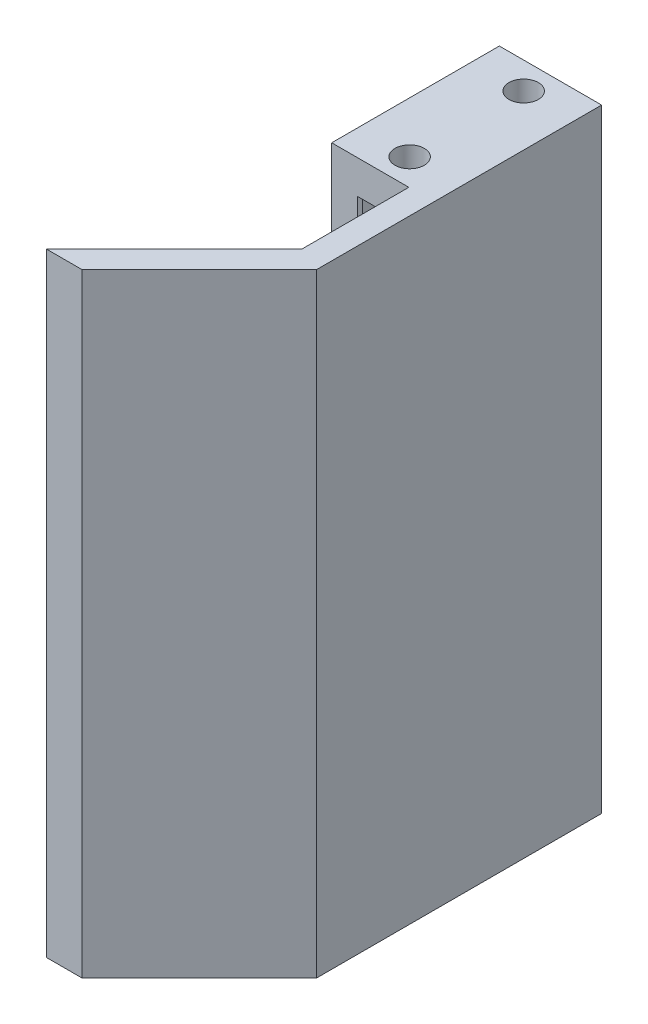
SolidWorks part; units mm, degrees
material "ABS"
ref_plane "前视基准面" through (0, 0, 0) normal (0, 0, 1) x (1, 0, 0)
ref_plane "上视基准面" through (0, 0, 0) normal (0, 1, 0) x (1, 0, 0)
ref_plane "右视基准面" through (0, 0, 0) normal (1, 0, 0) x (0, 0, -1)
other "Configuration Table"
sketch "草图1" plane through (0, 0, 0) normal (0, 1, 0) x (1, 0, 0)
  line L0 (1.5, -17) -> (-12.5, -31)
  line L1 (-1.5, 17) -> (1.5, 17)
  line L2 (-1.5, 17) -> (-1.5, -17)
  line L3 (-1.5, -17) -> (1.5, -17)
  line L4 (1.5, 17) -> (1.5, -17)
  line L5 (-1.5, 17) -> (1.5, -17) construction
  line L6 (-1.5, -17) -> (1.5, 17) construction
  line L7 (-12.5, -31) -> (-16.7426, -31)
  line L8 (-16.7426, -31) -> (-1.5, -15.7574)
  point P0 (0, 0)
  dimension "D1" = 3
  dimension "D2" = 3
  dimension "D3" = 48
  dimension "D4" = 14
  dimension "D5" = 135
extrude "凸台-拉伸1" add sketch "草图1" along normal blind 73.2
sketch "草图2" plane through (0, 73.2, 0) normal (0, 1, 0) x (1, 0, 0)
  line L1 (-1.5, 17) -> (-10.7, 17)
  line L2 (-1.5, 17) -> (-1.5, -3)
  line L3 (-1.5, -3) -> (-10.7, -3)
  line L4 (-10.7, 17) -> (-10.7, -3)
  dimension "D1" = 9.2
  dimension "D2" = 20
extrude "凸台-拉伸2" add sketch "草图2" against normal blind 12
sketch "草图4" plane through (0, 73.2, 0) normal (0, 1, 0) x (1, 0, 0)
  line L0 (-4.6, 17) -> (-4.6, -3) construction
  line L1 (-10.7, 17) -> (1.5, 17) construction
  line L2 (-10.7, -3) -> (-1.5, -3) construction
  line L3 (-4.6, 7) -> (1.5, 7) construction
  line L4 (-7.325, 17) -> (-1.875, 17) construction
  line L5 (-7.325, 17) -> (-7.325, 10.6) construction
  line L6 (-7.325, 10.6) -> (-1.875, 10.6) construction
  line L7 (-1.875, 17) -> (-1.875, 10.6) construction
  line L8 (1.5, 17) -> (1.5, -17) construction
  line L9 (-7.325, 3.4) -> (-1.875, 3.4) construction
  line L10 (-1.875, -3) -> (-1.875, 3.4) construction
  line L11 (-7.325, -3) -> (-1.875, -3) construction
  line L12 (-7.325, -3) -> (-7.325, 3.4) construction
  circle A0 centre (-4.6, 13.8) radius 1.75
  circle A2 centre (-4.6, 0.2) radius 1.75
  point P10 (-4.6, 10.6)
  dimension "D1" = 3.5
  dimension "D2" = 3.2
  dimension "D3" = 5.45
  dimension "D4" = 3.2
extrude "切除-拉伸1" cut sketch "草图4" against normal blind 20
ref_plane "基准面1" through (0, 69.2, 0) normal (0, 1, 0) x (1, 0, 0)
sketch "草图7" plane through (0, 69.2, 0) normal (0, 1, 0) x (1, 0, 0)
  line L1 (-7.325, 3.4) -> (-1.875, 3.4)
  line L2 (-7.325, 3.4) -> (-7.325, -3)
  line L3 (-7.325, -3) -> (-1.875, -3)
  line L4 (-1.875, 3.4) -> (-1.875, -3)
  line L5 (-7.225, 10.6) -> (-1.875, 10.6)
  line L6 (-7.225, 10.6) -> (-7.225, 17)
  line L7 (-7.225, 17) -> (-1.875, 17)
  line L8 (-1.875, 10.6) -> (-1.875, 17)
  dimension "D1" = 5.35
  dimension "D2" = 6.4
extrude "切除-拉伸2" cut sketch "草图7" against normal blind 5
ref_plane "基准面2" through (0, 36.6, 0) normal (0, 1, 0) x (1, 0, 0)
mirror "镜向1" about plane through (0, 36.6, 0) normal (0, 1, 0) of "切除-拉伸2", "切除-拉伸1", "凸台-拉伸2"
chamfer "倒角1" distance 0.3 angle 45 8 edges at (-7.325, 6.5, 3) (-1.875, 6.5, 3) (-7.225, 6.5, -17) (-1.875, 6.5, -17) (-7.225, 66.7, -17) (-1.875, 66.7, -17) (-7.325, 66.7, 3) (-1.875, 66.7, 3)
